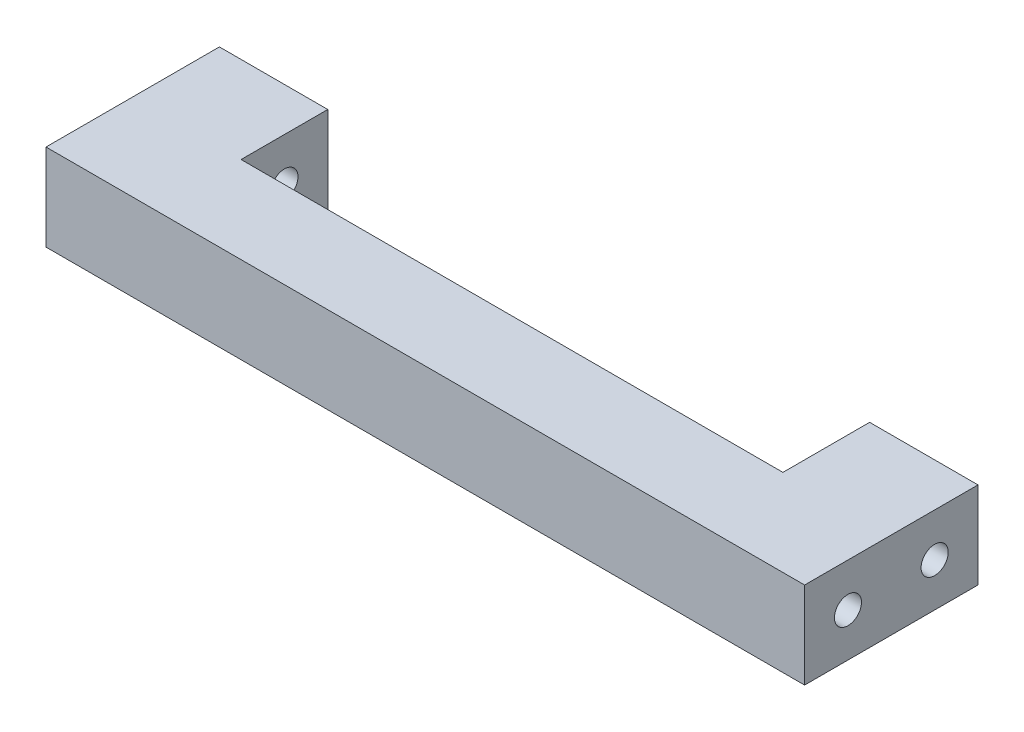
SolidWorks part; units mm, degrees
ref_plane "Front" through (0, 0, 0) normal (0, 0, 1) x (1, 0, 0)
ref_plane "Top" through (0, 0, 0) normal (0, 1, 0) x (1, 0, 0)
ref_plane "Right" through (0, 0, 0) normal (1, 0, 0) x (0, 0, -1)
sketch "草图1" plane through (0, 0, 0) normal (0, 1, 0) x (1, 0, 0)
  line L1 (35, -8) -> (-35, -8)
  line L2 (35, -8) -> (35, 8)
  line L3 (35, 8) -> (-35, 8)
  line L4 (-35, -8) -> (-35, 8)
  line L5 (35, -8) -> (-35, 8) construction
  line L6 (35, 8) -> (-35, -8) construction
  point P0 (0, 0)
  dimension "D1" = 16
  dimension "D2" = 70
extrude "凸台-拉伸1" add sketch "草图1" along normal blind 8
sketch "草图2" plane through (0, 8, 0) normal (0, 1, 0) x (1, 0, 0)
  line L0 (35, 8) -> (-35, 8) construction
  line L1 (25, 8) -> (-25, 8)
  line L2 (25, 8) -> (25, 0)
  line L3 (25, 0) -> (-25, 0)
  line L4 (-25, 8) -> (-25, 0)
  line L5 (25, 8) -> (-25, 0) construction
  line L6 (25, 0) -> (-25, 8) construction
  line L7 (-35, 8) -> (-35, -8) construction
  line L8 (35, -8) -> (35, 8) construction
  line L9 (-35, -8) -> (35, -8) construction
  point P0 (0, 4)
  dimension "D1" = 10
  dimension "D2" = 10
  dimension "D3" = 8
extrude "切除-拉伸1" cut sketch "草图2" against normal through all
sketch "草图3" plane through (35, 0, 0) normal (1, 0, 0) x (0, 0, -1)
  line L0 (-8, 4) -> (8, 4) construction
  line L1 (-8, 8) -> (-8, 0) construction
  line L2 (8, 8) -> (8, 0) construction
  line L3 (0, 8) -> (0, 0) construction
  line L4 (-8, 8) -> (8, 8) construction
  line L5 (-8, 0) -> (8, 0) construction
  circle A0 centre (-4, 4) radius 1.25
  circle A1 centre (4, 4) radius 1.25
  point P16 (0, 0)
  dimension "D1" = 2.5
  dimension "D2" = 2.5
  dimension "D3" = 8
extrude "切除-拉伸2" cut sketch "草图3" against normal blind 20
mirror "镜向1" about plane through (0, 0, 0) normal (1, 0, 0) of "切除-拉伸2"
